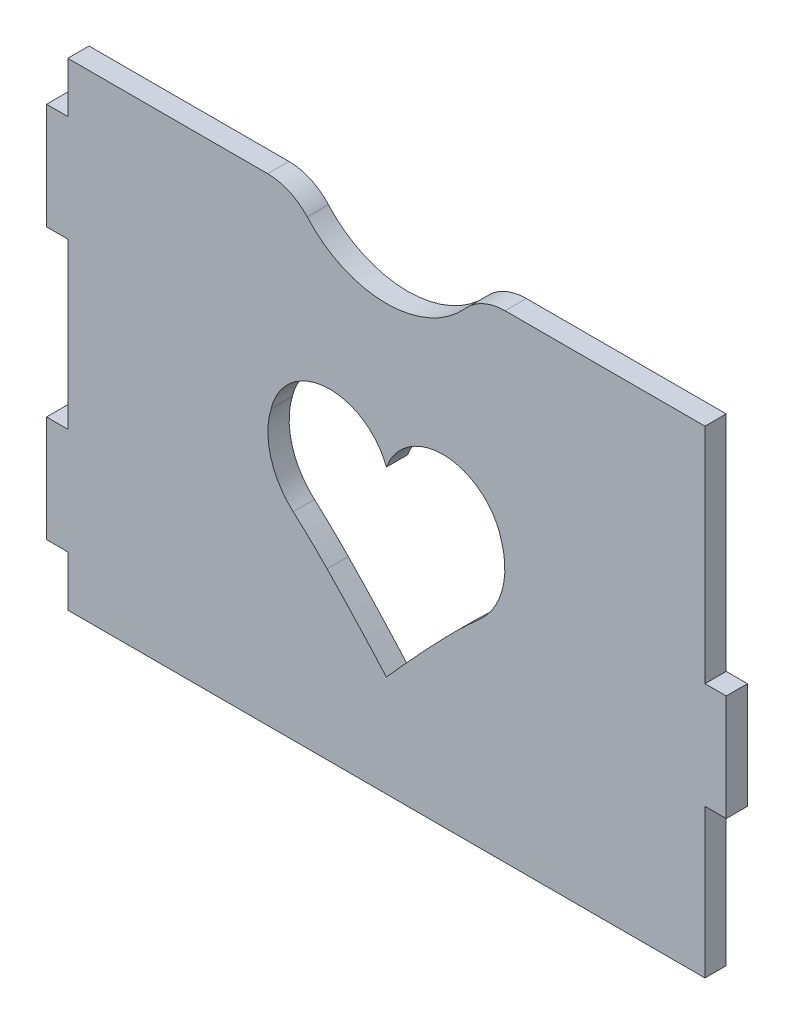
SolidWorks part; units mm, degrees
ref_plane "Спереди" through (0, 0, 0) normal (0, 0, 1) x (1, 0, 0)
ref_plane "Сверху" through (0, 0, 0) normal (0, 1, 0) x (1, 0, 0)
ref_plane "Справа" through (0, 0, 0) normal (1, 0, 0) x (0, 0, -1)
sketch "Эскиз1" plane through (0, 0, 0) normal (0, 0, 1) x (1, 0, 0)
  line L0 (0, 0) -> (-60, 0) construction
  line L1 (-60, 45) -> (-22.3607, 45)
  line L2 (-60, 45) -> (-60, -45)
  line L3 (-60, -45) -> (60, -45)
  line L4 (60, 45) -> (60, -45)
  line L5 (-60, 45) -> (60, -45) construction
  line L6 (-60, -45) -> (60, 45) construction
  line L7 (-60, -15.5) -> (-64, -15.5)
  line L8 (-60, -15.5) -> (-60, -35.5)
  line L9 (-60, -35.5) -> (-64, -35.5)
  line L10 (-64, -15.5) -> (-64, -35.5)
  line L11 (0, 0) -> (0, -45) construction
  line L12 (-60, 35.5) -> (-64, 35.5)
  line L13 (-64, 15.5) -> (-64, 35.5)
  line L14 (-60, 15.5) -> (-64, 15.5)
  line L15 (-60, 15.5) -> (-60, 35.5)
  line L24 (-64, -25.5) -> (-60, -25.5) construction
  line L33 (-64, 25.5) -> (-60, 25.5) construction
  line L34 (22.3607, 45) -> (60, 45)
  line L36 (0, 0) -> (0, 35) construction
  line L39 (60, -17) -> (64, -17)
  line L40 (60, -17) -> (60, 3)
  line L41 (60, 3) -> (64, 3)
  line L42 (64, -17) -> (64, 3)
  line L43 (64, -7) -> (60, -7) construction
  arc A0 (-14.9071, 41.6667) -> (14.9071, 41.6667) centre (0, 55) ccw
  arc A1 (-22.3607, 45) -> (-14.9071, 41.6667) centre (-22.3607, 35) cw
  arc A2 (14.9071, 41.6667) -> (22.3607, 45) centre (22.3607, 35) cw
  point P0 (0, 0)
  point P36 (17.3205, 45)
  point P51 (-144.5623, -13.8677)
  line B0 (0, 8.325) -> (0, -25.9208) construction
  arc B1 (0, 8.325) -> (-21.6936, 7.0386) centre (-10.6493, 4.3505) ccw
  arc B2 (-21.6936, 7.0386) -> (-17.5466, -7.727) centre (-8.0849, 2.8956) ccw
  arc B3 (-11.1634, -13.8491) -> (0, -25.9208) centre (-266.9664, -261.6019) cw
  arc B4 (-17.5466, -7.727) -> (-11.1634, -13.8491) centre (-97.3618, -97.3347) cw
  arc B5 (17.5466, -7.727) -> (11.1634, -13.8491) centre (97.3618, -97.3347) ccw
  arc B6 (11.1634, -13.8491) -> (0, -25.9208) centre (266.9664, -261.6019) ccw
  arc B7 (21.6936, 7.0386) -> (17.5466, -7.727) centre (8.0849, 2.8956) cw
  arc B8 (0, 8.325) -> (21.6936, 7.0386) centre (10.6493, 4.3505) cw
  dimension "D7" = 40
  dimension "D9" = 10
  dimension "D10" = 38
  dimension "D1" = 120
  dimension "D2" = 90
  dimension "D3" = 4
  dimension "D4" = 20
  dimension "D5" = 19.5
  dimension "D6" = 51
  dimension "D8" = 10
  dimension "D11" = 20
  dimension "D12" = 4
sketch_block_instance "Блок1-1"
sketch_block "Блок1"
extrude "Бобышка-Вытянуть1" add sketch "Эскиз1" along normal blind 4
